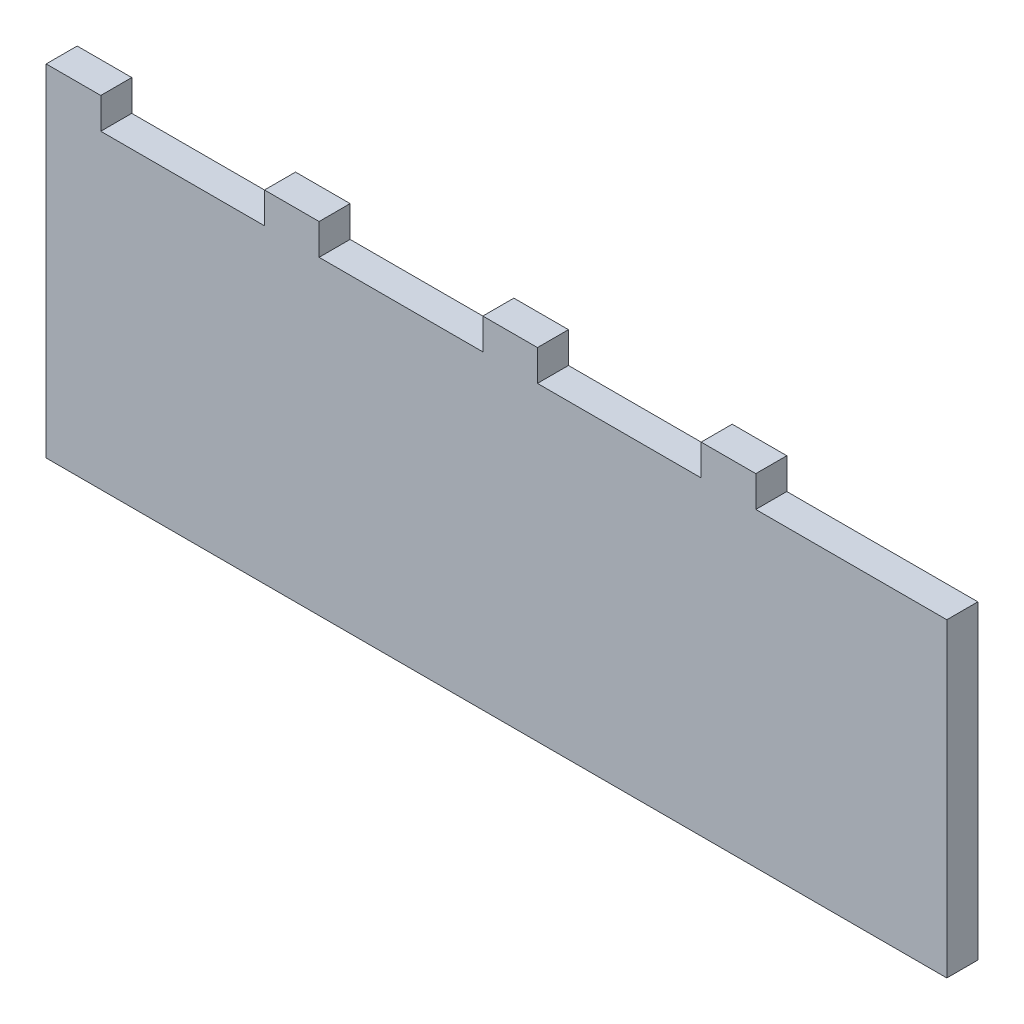
SolidWorks part; units mm, degrees
ref_plane "Front Plane" through (0, 0, 0) normal (0, 0, 1) x (1, 0, 0)
ref_plane "Top Plane" through (0, 0, 0) normal (0, 1, 0) x (1, 0, 0)
ref_plane "Right Plane" through (0, 0, 0) normal (1, 0, 0) x (0, 0, -1)
sketch "Sketch1" plane through (0, 0, 0) normal (0, 0, 1) x (1, 0, 0)
  line L0 (-379.0181, 0) -> (18571.8862, 0) construction
  line L1 (-2.2, 0) -> (2.2, 0)
  line L2 (-2.2, 0) -> (-2.2, 27.5)
  line L3 (-2.2, 27.5) -> (2.2, 27.5)
  line L4 (2.2, 25) -> (2.2, 27.5)
  line L5 (15.3929, 25) -> (15.3929, 27.5)
  line L6 (15.3929, 0) -> (19.7929, 0)
  line L7 (19.7929, 25) -> (19.7929, 27.5)
  line L8 (15.3929, 27.5) -> (19.7929, 27.5)
  line L9 (32.9858, 25) -> (32.9858, 27.5)
  line L10 (32.9858, 0) -> (37.3858, 0)
  line L11 (37.3858, 25) -> (37.3858, 27.5)
  line L12 (32.9858, 27.5) -> (37.3858, 27.5)
  line L13 (50.5787, 25) -> (50.5787, 27.5)
  line L14 (50.5787, 0) -> (54.9787, 0)
  line L15 (54.9787, 25) -> (54.9787, 27.5)
  line L16 (50.5787, 27.5) -> (54.9787, 27.5)
  line L17 (-2.2, 0) -> (15.3929, 0) construction
  line L18 (0, 0) -> (70.3717, 0)
  line L19 (70.3717, 0) -> (70.3717, 25)
  line L20 (70.3717, 25) -> (54.9787, 25)
  line L21 (50.5787, 25) -> (37.3858, 25)
  line L22 (32.9858, 25) -> (19.7929, 25)
  line L23 (15.3929, 25) -> (2.2, 25)
  point P5 (0, 0)
  point P32 (0, 0)
  point P33 (0, 0)
  point P34 (0, 0)
  point P35 (15.3929, 25)
  point P36 (0, 0)
  dimension "D1" = 4.4
  dimension "D2" = 27.5
  dimension "D4" = 17.5929
  dimension "D5" = 70.3717
  dimension "D6" = 2.5
  dimension "D7" = 4.4
  dimension "D3" = 4
extrude "Boss-Extrude1" add sketch "Sketch1" along normal blind 2.5 contours L5 L23 L4 L3 L2 L1 L18 L6 L10 L14 L19 L20 L15 L16 L13 L21 L11 L12 L9 L22 L7 L8
